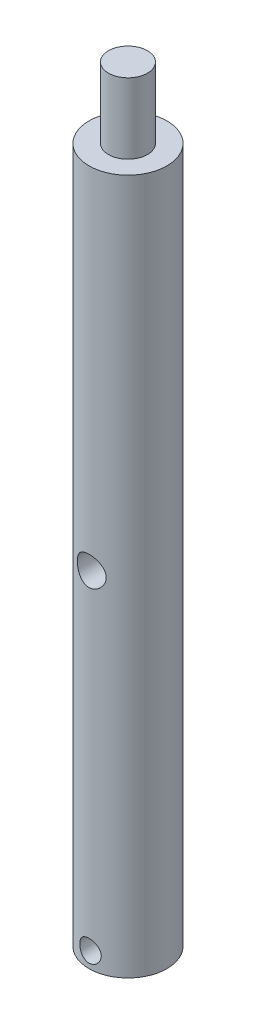
SolidWorks part; units mm, degrees
material "1023 Carbon Steel Sheet (SS)"
ref_plane "Front Plane" through (0, 0, 0) normal (0, 0, 1) x (1, 0, 0)
ref_plane "Top Plane" through (0, 0, 0) normal (0, 1, 0) x (1, 0, 0)
ref_plane "Right Plane" through (0, 0, 0) normal (1, 0, 0) x (0, 0, -1)
sketch "Sketch1" plane through (0, 0, 0) normal (0, 1, 0) x (1, 0, 0)
  circle A0 centre (0, 0) radius 6.35
  dimension "D1" = 12.7
extrude "Boss-Extrude1" add sketch "Sketch1" along normal mid plane 124.7902
sketch "Sketch3" plane through (0, 62.3951, 0) normal (0, 1, 0) x (1, 0, 0)
  circle A0 centre (0, 0) radius 3.175
  dimension "D1" = 6.35
extrude "Cut-Extrude1" cut sketch "Sketch3" against normal blind 11.4935 flip side to cut
sketch "Sketch7" plane through (0, 0, 0) normal (0, 0, 1) x (1, 0, 0)
  line L0 (-6.35, -62.3951) -> (6.35, -62.3951) construction
  circle A0 centre (0, -59.8551) radius 1.7526
  dimension "D1" = 3.5052
  dimension "D2" = 2.54
extrude "Cut-Extrude3" cut sketch "Sketch7" against normal mid plane 19.05
sketch "Sketch9" plane through (0, 0, 0) normal (1, 0, 0) x (0, 0, -1)
  line L0 (6.35, 50.9016) -> (-6.35, 50.9016) construction
  circle A0 centre (0, -6.2484) radius 2.3495
  dimension "D1" = 57.15
  dimension "D2" = 4.699
sketch "Sketch10" plane through (0, 0, 0) normal (0, 0, 1) x (1, 0, 0)
  line L0 (0, -8.5979) -> (0, -3.8989) construction
  circle A0 centre (0, -6.2484) radius 2.3495
  dimension "D1" = 4.699
extrude "Cut-Extrude6" cut sketch "Sketch10" against normal mid plane 12.7
